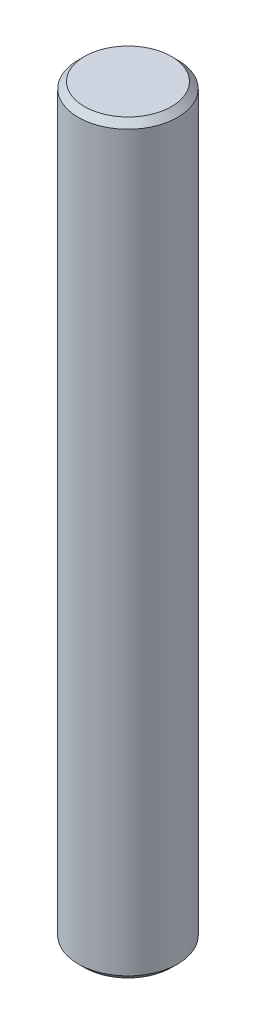
SolidWorks part; units mm, degrees
material "AISI 1045 Steel, cold drawn"
ref_plane "Front Plane" through (0, 0, 0) normal (0, 0, 1) x (1, 0, 0)
ref_plane "Top Plane" through (0, 0, 0) normal (0, 1, 0) x (1, 0, 0)
ref_plane "Right Plane" through (0, 0, 0) normal (1, 0, 0) x (0, 0, -1)
sketch "Sketch1" plane through (0, 0, 0) normal (0, 1, 0) x (1, 0, 0)
  circle A0 centre (0, 0) radius 2
  dimension "D1" = 4
extrude "Boss-Extrude1" add sketch "Sketch1" along normal mid plane 30
chamfer "Chamfer1" distance 0.25 angle 45 2 edges at (0, -15, 2) (0, 15, 2)
